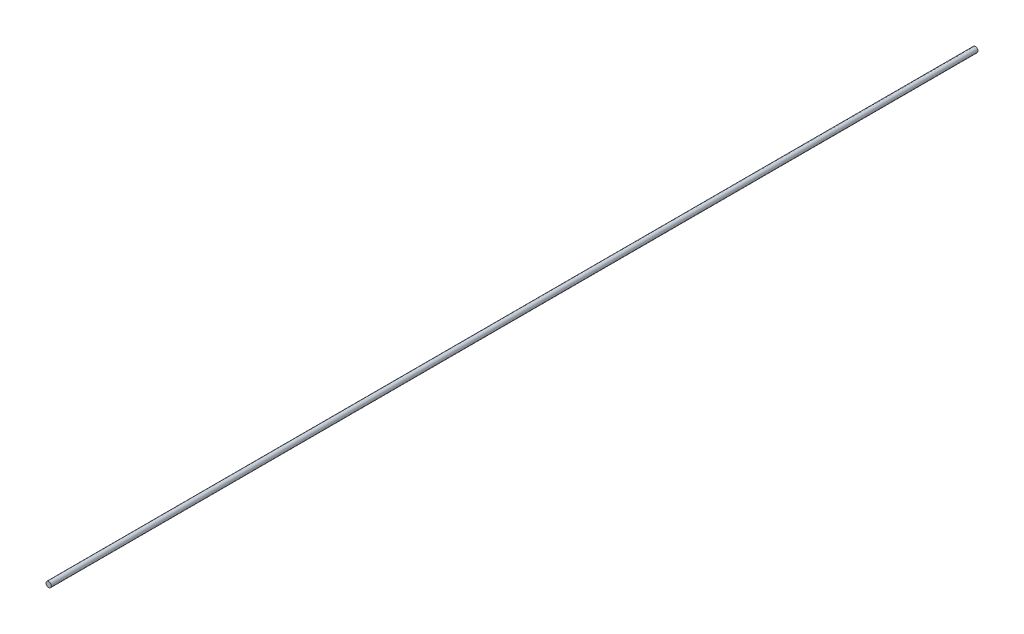
SolidWorks part; units mm, degrees
ref_plane "前视基准面" through (0, 0, 0) normal (0, 0, 1) x (1, 0, 0)
ref_plane "上视基准面" through (0, 0, 0) normal (0, 1, 0) x (1, 0, 0)
ref_plane "右视基准面" through (0, 0, 0) normal (1, 0, 0) x (0, 0, -1)
other "Configuration Table"
sketch "草图1" plane through (0, 0, 0) normal (0, 0, 1) x (1, 0, 0)
  circle A0 centre (0, 0) radius 0.4
extrude "D0p8钢索直线跨度" add sketch "草图1" along normal blind 140.2554
